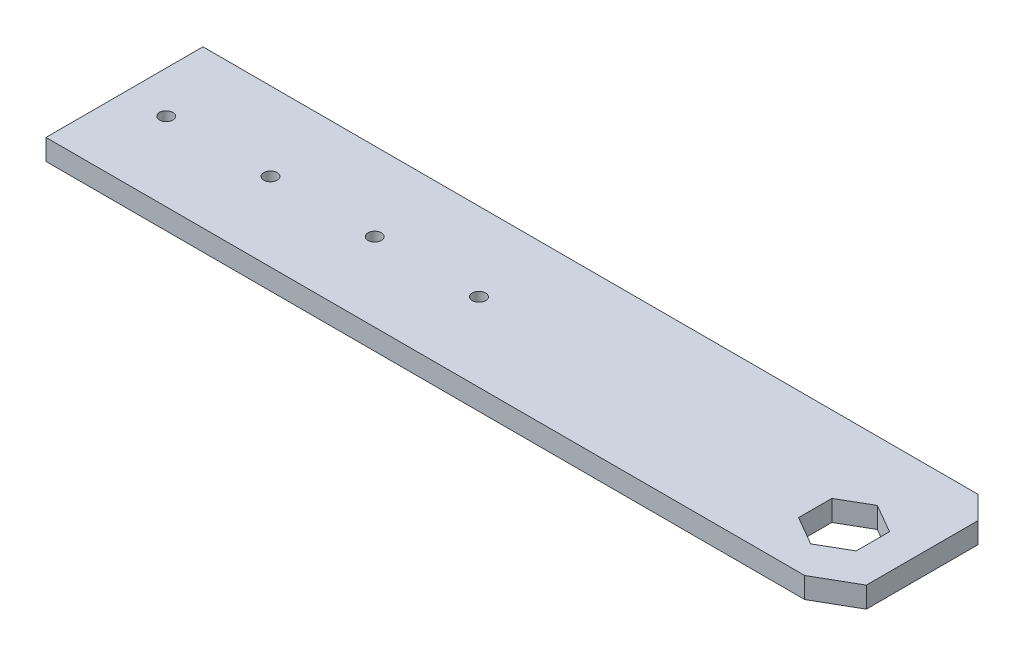
SolidWorks part; units mm, degrees
ref_plane "Front Plane" through (0, 0, 0) normal (0, 0, 1) x (1, 0, 0)
ref_plane "Top Plane" through (0, 0, 0) normal (0, 1, 0) x (1, 0, 0)
ref_plane "Right Plane" through (0, 0, 0) normal (1, 0, 0) x (0, 0, -1)
sketch "Sketch1" plane through (0, 0, 0) normal (0, 1, 0) x (1, 0, 0)
  line L0 (23.3189, 45.3036) -> (28.7889, 39.8236)
  line L1 (13.5639, 14.9541) -> (20.4789, 18.9465)
  line L2 (20.4789, 18.9465) -> (20.4789, 26.9313)
  line L3 (20.4789, 26.9313) -> (13.5639, 30.9236)
  line L4 (13.5639, 30.9236) -> (6.6489, 26.9313)
  line L5 (6.6489, 26.9313) -> (6.6489, 18.9465)
  line L6 (6.6489, 18.9465) -> (13.5639, 14.9541)
  line L7 (-17.9811, 45.3036) -> (28.7889, 45.3036)
  line L8 (-17.9811, 45.3036) -> (-17.9811, 7.6741)
  line L9 (-17.9811, 7.6741) -> (28.7889, 7.6741)
  line L10 (28.7889, 45.3036) -> (28.7889, 7.6741)
  line L11 (28.7889, 39.8236) -> (28.7889, 45.3036)
  line L12 (28.7889, 13.0536) -> (19.4089, 7.6741)
  line L14 (-17.9811, 45.3036) -> (-162.5111, 45.3036)
  line L15 (-17.9811, 45.3036) -> (-17.9811, 7.6741)
  line L16 (-17.9811, 7.6741) -> (-162.5111, 7.6741)
  line L17 (-162.5111, 45.3036) -> (-162.5111, 7.6741)
  circle A0 centre (13.5639, 22.9389) radius 6.915 construction
  circle A1 centre (-152.5111, 26.4886) radius 1.6
  circle A2 centre (-127.5111, 26.4886) radius 1.6
  circle A3 centre (-102.5111, 26.4886) radius 1.6
  circle A4 centre (-77.5111, 26.4886) radius 1.6
  point P26 (0, 0)
  point P29 (-94.466, 28.9635)
  dimension "D9" = 13.83
  dimension "D11" = 3.2
  dimension "D12" = 3.2
  dimension "D13" = 3.2
  dimension "D14" = 3.2
  dimension "D1" = 8.31
  dimension "D2" = 14.38
  dimension "D3" = 7.28
  dimension "D4" = 24.63
  dimension "D5" = 5.47
  dimension "D6" = 5.48
  dimension "D7" = 26.77
  dimension "D8" = 9.38
  dimension "D10" = 144.53
  dimension "D15" = 10
  dimension "D16" = 25
  dimension "D17" = 25
  dimension "D18" = 25
  dimension "D19" = 18.815
extrude "Boss-Extrude1" add sketch "Sketch1" along normal blind 5 contours L14 L17 L16 L8 A4 A3 A2 A1 | L12 L10 L0 L7 L8 L9 L6 L5 L4 L3 L2 L1
